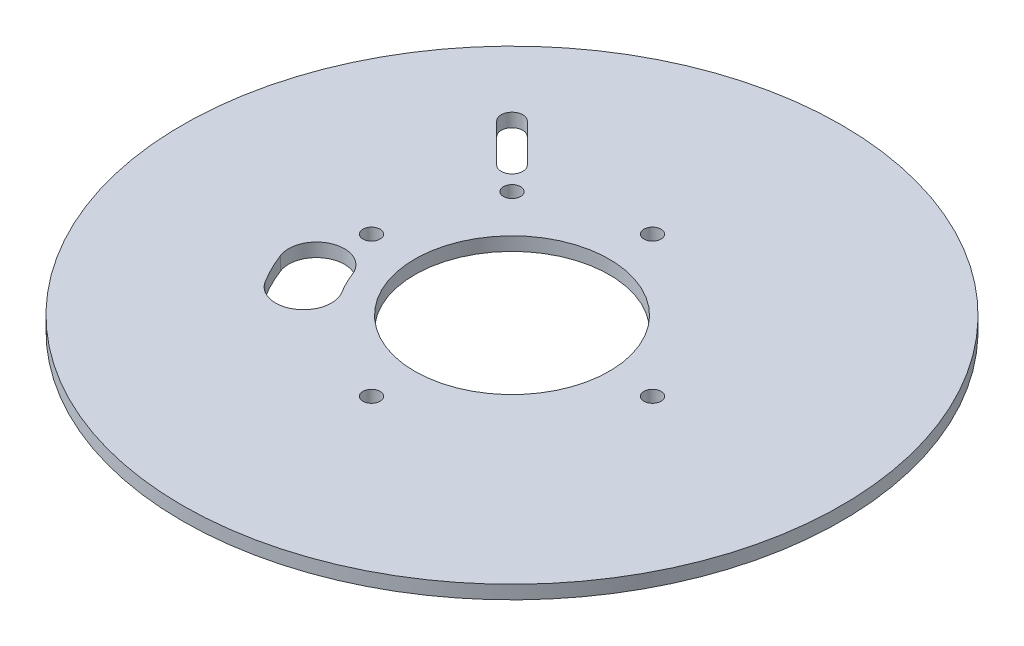
SolidWorks part; units mm, degrees
ref_plane "Front" through (0, 0, 0) normal (0, 0, 1) x (1, 0, 0)
ref_plane "Top" through (0, 0, 0) normal (0, 1, 0) x (1, 0, 0)
ref_plane "Right" through (0, 0, 0) normal (1, 0, 0) x (0, 0, -1)
sketch "Sketch1" plane through (0, 0, 0) normal (0, 1, 0) x (1, 0, 0)
  circle A0 centre (0, 0) radius 77.46
  dimension "D1" = 154.92
extrude "Boss-Extrude1" add sketch "Sketch1" along normal blind 3.175
sketch "Sketch2" plane through (0, 3.175, 0) normal (0, 1, 0) x (1, 0, 0)
  circle A0 centre (0, 0) radius 22.86
  dimension "D1" = 45.72
extrude "Cut-Extrude1" [suppressed] cut sketch "Sketch2" against normal through all
hole_wizard "M3 Clearance Hole1" [suppressed] positions "Sketch4" profile "Sketch3" hole size "M3" standard "ANSI Metric"
sketch "Sketch4" plane through (0, 3.175, 0) normal (0, 1, 0) x (1, 0, 0)
  circle A0 centre (0, 0) radius 27 construction
  point P0 (-27, 0)
  point P2 (0, 27)
  point P4 (27, 0)
  point P6 (0, -27)
  dimension "D1" = 54
sketch "Sketch3" plane through (-27, 3.175, 0) normal (1, 0, 0) x (0, 0, 1)
  line L0 (0, 0) -> (0, 3.175)
  line L1 (0, 3.175) -> (1.7, 3.175)
  line L2 (1.7, 3.175) -> (1.7, 0)
  line L5 (1.7, 0) -> (0, 0)
  line L11 (0, -6.35) -> (0, 107.95) construction
  dimension "Thru Hole Dia." = 3.4
  dimension "Thru Hole Depth" = 3.175
sketch "Sketch5" plane through (0, 0, 0) normal (0, -1, 0) x (-1, 0, 0)
  line L0 (0, 0) -> (116.3694, 0) construction
  line L1 (76.4147, 28.5) -> (66.4147, 28.5)
  line L2 (76.4147, 28.5) -> (76.4147, 31.5)
  line L3 (76.4147, 31.5) -> (66.4147, 31.5)
  line L4 (66.4147, 28.5) -> (66.4147, 31.5)
  line L5 (76.4147, 28.5) -> (66.4147, 31.5) construction
  line L6 (76.4147, 31.5) -> (66.4147, 28.5) construction
  line L7 (76.4147, -28.5) -> (76.4147, -31.5)
  line L8 (76.4147, -28.5) -> (66.4147, -28.5)
  line L9 (66.4147, -28.5) -> (66.4147, -31.5)
  line L10 (76.4147, -31.5) -> (66.4147, -31.5)
  circle A0 centre (0, 0) radius 77.46 construction
  point P0 (71.4147, 30)
  dimension "D1" = 3
  dimension "D2" = 10
  dimension "D3" = 30
extrude "Cut-Extrude2" [suppressed] cut sketch "Sketch5" against normal through all
hole_wizard "M3 Clearance Slot1" [suppressed] positions "Sketch7" profile "Sketch8" size "M3" standard "ANSI Metric"
sketch "Sketch7" plane through (0, 0, 0) normal (0, -1, 0) x (-1, 0, 0)
  line L0 (0, 0) -> (71.3755, 0) construction
  line L1 (55, -30) -> (25, -30) construction
  point P0 (40, -30)
  dimension "D1" = 40
  dimension "D2" = 30
  dimension "D3" = 30
sketch "Sketch8" plane through (-40, 0, 30) normal (1, 0, 0) x (0, 0, -1)
  line L0 (0, 0) -> (0, 26.4215)
  line L1 (0, 26.4215) -> (1.7, 25.4)
  line L2 (1.7, 25.4) -> (1.7, 0)
  line L5 (1.7, 0) -> (0, 0)
  line L10 (0, 26.4215) -> (-1.7, 25.4) construction
  line L11 (0, -6.35) -> (0, 107.95) construction
  dimension "Hole Dia." = 3.4
  dimension "Hole Depth" = 25.4
  dimension "Drill Angle" = 118
hole_wizard "M3 Clearance Hole2" [suppressed] positions "Sketch11" profile "Sketch12" hole size "M3" standard "ANSI Metric"
sketch "Sketch11" [suppressed] plane through (0, 3.175, 0) normal (0, 1, 0) x (1, 0, 0)
  line L0 (-53.3, -28.3) -> (-53.3, 14.1687) construction
  point P0 (-53.3, 30)
  dimension "D1" = 30
sketch "Sketch12" plane through (-53.3, 3.175, -30) normal (1, 0, 0) x (0, 0, 1)
  line L0 (0, 0) -> (0, 3.175)
  line L1 (0, 3.175) -> (1.7, 3.175)
  line L2 (1.7, 3.175) -> (1.7, 0)
  line L5 (1.7, 0) -> (0, 0)
  line L11 (0, -6.35) -> (0, 107.95) construction
  dimension "Thru Hole Dia." = 3.4
  dimension "Thru Hole Depth" = 3.175
sketch "Sketch13" [suppressed] plane through (0, 3.175, 0) normal (0, 1, 0) x (1, 0, 0)
  line L0 (0, 0) -> (0, 33.02) construction
  circle A0 centre (0, 0) radius 33.02 construction
  circle A1 centre (0, 0) radius 22.86 construction
  circle A2 centre (0, 33.02) radius 2.0193
  circle A3 centre (33.02, 0) radius 2.0193
  circle A4 centre (0, -33.02) radius 2.0193
  circle A5 centre (-33.02, 0) radius 2.0193
  point P16 (0, 0)
  dimension "D1" = 10.16
  dimension "D2" = 4.0386
  dimension "D3" = 4
extrude "Cut-Extrude3" [suppressed] cut sketch "Sketch13" against normal up to next
extrude "Cut-Extrude9" [suppressed] cut sketch "Sketch19" against normal through all
sketch "Sketch19" plane through (-73.7688, 3.175, -121.0804) normal (0, 1, 0) x (1, 0, 0)
  circle A1 centre (48.605, -95.9166) radius 2.0193 construction
  circle A3 centre (73.7688, -121.0804) radius 22.86 construction
  circle A4 centre (73.7688, -121.0804) radius 35.587 construction
  arc A5 (40.7129, -134.2614) -> (42.8303, -138.6656) centre (73.7688, -121.0804) ccw construction
  arc A6 (33.7184, -137.0504) -> (36.2838, -142.3866) centre (73.7688, -121.0804) ccw
  arc A7 (47.7074, -131.4723) -> (49.3768, -134.9446) centre (73.7688, -121.0804) ccw
  arc A8 (47.7074, -131.4723) -> (33.7184, -137.0504) centre (40.7129, -134.2614) ccw
  arc A9 (36.2838, -142.3866) -> (49.3768, -134.9446) centre (42.8303, -138.6656) ccw
  point P9 (41.6959, -136.4999)
extrude "Cut-Extrude10" cut sketch "Sketch20" against normal through all
sketch "Sketch20" plane through (-73.7688, 3.175, -121.0804) normal (0, 1, 0) x (1, 0, 0)
  line L0 (73.7688, -121.0804) -> (73.7688, -88.0604) construction
  circle A1 centre (73.7688, -121.0804) radius 77.46 construction
  circle A2 centre (73.7688, -121.0804) radius 22.86
  circle A3 centre (73.7688, -88.0604) radius 2.0193
  circle A4 centre (106.7888, -121.0804) radius 2.0193
  circle A5 centre (73.7688, -154.1004) radius 2.0193
  circle A6 centre (40.7488, -121.0804) radius 2.0193
  point P4 (73.7688, -98.2204)
  point P16 (73.7688, -121.0804)
extrude "Cut-Extrude11" cut sketch "Sketch21" against normal blind 3.175
sketch "Sketch21" plane through (-73.7688, 3.175, -121.0804) normal (0, 1, 0) x (1, 0, 0)
  line L0 (43.2169, -90.5284) -> (34.2366, -81.5481) construction
  line L1 (41.4208, -92.3245) -> (32.4406, -83.3442)
  line L2 (45.0129, -88.7324) -> (36.0327, -79.7521)
  arc A1 (41.4208, -92.3245) -> (45.0129, -88.7324) centre (43.2169, -90.5284) ccw construction
  arc A2 (41.4208, -92.3245) -> (45.0129, -88.7324) centre (43.2169, -90.5284) ccw
  arc A3 (36.0327, -79.7521) -> (32.4406, -83.3442) centre (34.2366, -81.5481) ccw
  point P3 (38.7267, -86.0383)
extrude "Cut-Extrude12" cut sketch "Sketch22" against normal through all
sketch "Sketch22" plane through (-73.7688, 3.175, -121.0804) normal (0, 1, 0) x (1, 0, 0)
  line L0 (43.2169, -90.5284) -> (48.605, -95.9166) construction
  arc A1 (41.4208, -92.3245) -> (45.0129, -88.7324) centre (43.2169, -90.5284) ccw construction
  circle A2 centre (48.605, -95.9166) radius 2.0193
extrude "Cut-Extrude13" cut sketch "Sketch23" against normal through all
sketch "Sketch23" plane through (-73.7688, 3.175, -121.0804) normal (0, 1, 0) x (1, 0, 0)
  circle A2 centre (73.7688, -121.0804) radius 22.86 construction
  circle A3 centre (48.605, -95.9166) radius 2.0193 construction
  circle A4 centre (73.7688, -121.0804) radius 35.587 construction
  arc A5 (40.5263, -133.7834) -> (43.5223, -139.8309) centre (73.7688, -121.0804) ccw construction
  arc A6 (34.406, -136.1222) -> (37.9536, -143.283) centre (73.7688, -121.0804) ccw
  arc A7 (46.6466, -131.4446) -> (49.091, -136.3787) centre (73.7688, -121.0804) ccw
  arc A8 (46.6466, -131.4446) -> (34.406, -136.1222) centre (40.5263, -133.7834) ccw
  arc A9 (37.9536, -143.283) -> (49.091, -136.3787) centre (43.5223, -139.8309) ccw
  point P9 (41.8806, -136.8783)
